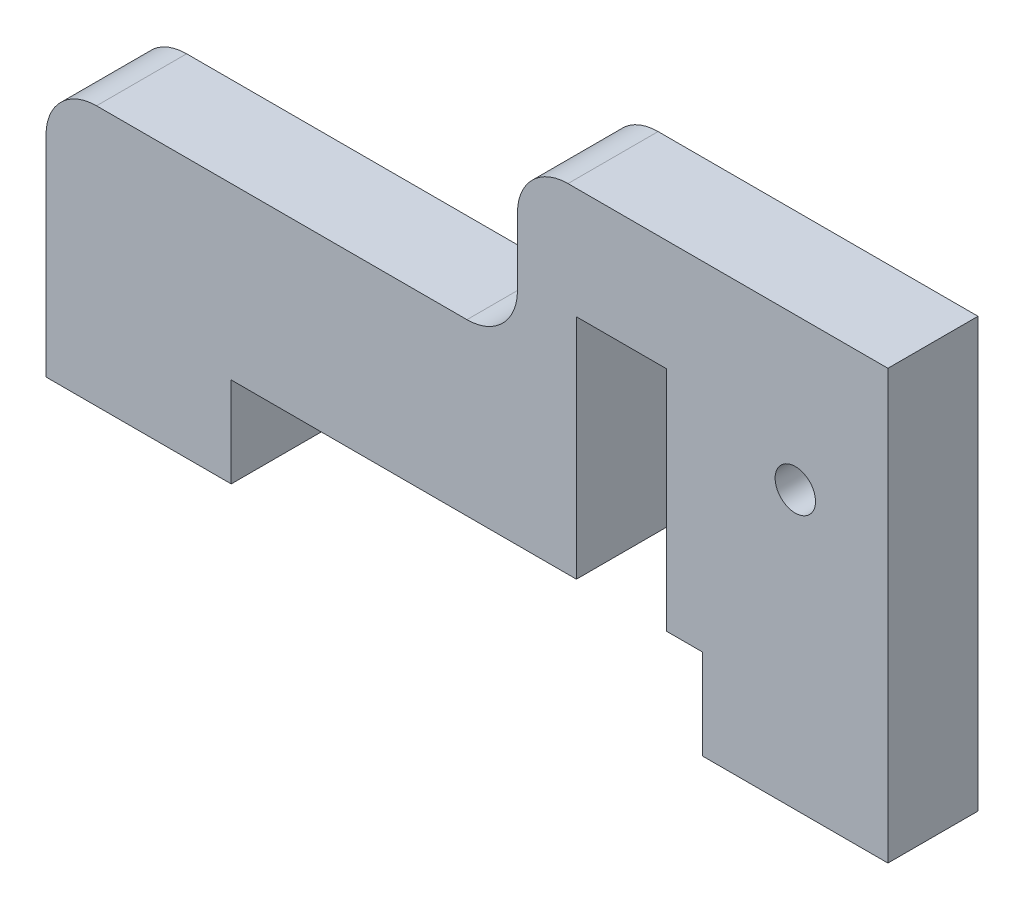
SolidWorks part; units mm, degrees
ref_plane "Front Plane" through (0, 0, 0) normal (0, 0, 1) x (1, 0, 0)
ref_plane "Top Plane" through (0, 0, 0) normal (0, 1, 0) x (1, 0, 0)
ref_plane "Right Plane" through (0, 0, 0) normal (1, 0, 0) x (0, 0, -1)
sketch "Model" plane through (0, 0, 0) normal (0, 0, 1) x (1, 0, 0)
  line L0 (39, 0) -> (50, 0)
  line L1 (0, 0) -> (11, 0)
  line L2 (0, 0) -> (0, 12.45)
  line L3 (31, 25.45) -> (50, 25.45)
  line L4 (50, 0) -> (50, 25.45)
  line L5 (44.5, 0) -> (44.5, 25.45) construction
  line L6 (11, 0) -> (11, 5.35)
  line L7 (11, 5.35) -> (31.5, 5.35)
  line L8 (39, 0) -> (39, 5.35)
  line L9 (36.85, 5.35) -> (39, 5.35)
  line L11 (3, 15.45) -> (25, 15.45)
  line L12 (28, 22.45) -> (28, 18.45)
  line L13 (31.5, 5.35) -> (31.5, 18.85)
  line L14 (31.5, 18.85) -> (36.85, 18.85)
  line L15 (36.85, 5.35) -> (36.85, 18.85)
  arc A0 (3, 15.45) -> (0, 12.45) centre (3, 12.45) ccw
  arc A1 (25, 15.45) -> (28, 18.45) centre (25, 18.45) ccw
  arc A2 (31, 25.45) -> (28, 22.45) centre (31, 22.45) ccw
  circle A3 centre (44.5, 16.45) radius 1.2
  dimension "D4" = 3
  dimension "D21" = 2.4
  dimension "D6" = 22
  dimension "D8" = 50
  dimension "D10" = 5.35
  dimension "D14" = 28
  dimension "D17" = 25.45
  dimension "D19" = 10
  dimension "D24" = 1
  dimension "D26" = 5.35
  dimension "D28" = 13.5
  dimension "D32" = 3.5
extrude "Boss-Extrude1" add sketch "Model" along normal blind 5.35
equation "\"mdfthick\"=5.35"
equation "\"D10@Model\"=\"mdfthick\""
equation "\"D26@Model\"=\"mdfthick\""
equation "\"D1@Boss-Extrude1\"=\"mdfthick\""
